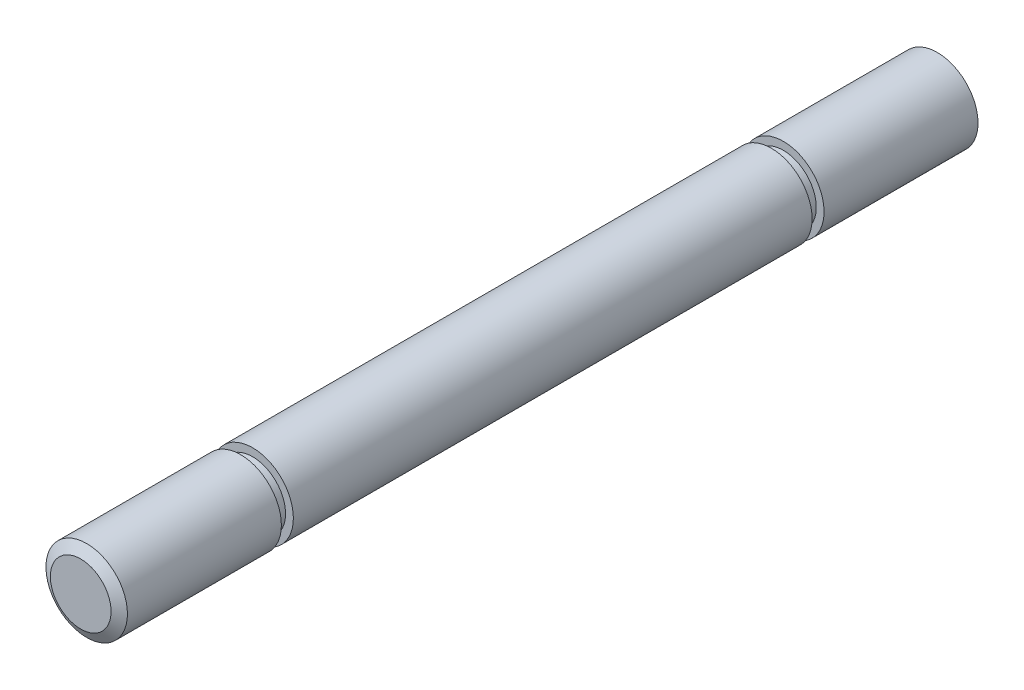
SolidWorks part; units mm, degrees
material "1.2210 (115CrV3)"
ref_plane "Front Plane" through (0, 0, 0) normal (0, 0, 1) x (1, 0, 0)
ref_plane "Top Plane" through (0, 0, 0) normal (0, 1, 0) x (1, 0, 0)
ref_plane "Right Plane" through (0, 0, 0) normal (1, 0, 0) x (0, 0, -1)
sketch "Sketch1" plane through (0, 0, 0) normal (1, 0, 0) x (0, 0, -1)
  line L0 (-36, 0) -> (-36, 3.4)
  line L1 (-36, 3.4) -> (2.4322, 3.4)
  line L5 (2.4322, 3.4) -> (36, 3.4)
  line L6 (36, 3.4) -> (36, 0)
  line L7 (36, 0) -> (-36, 0)
  line L8 (-36, 0) -> (-33.2337, 0) construction
  point P8 (0, 0)
  dimension "D1" = 6.8
  dimension "D2" = 72
revolve "Revolve1" add sketch "Sketch1" angle 360 about L8
chamfer "Chamfer1" distance 0.5 angle 60 2 edges at (0, -3.4, 36) (0, -3.4, -36)
sketch "Sketch2" plane through (0, 0, -36) normal (0, 0, -1) x (-1, 0, 0)
  circle A0 centre (0, 0) radius 2.75
  point P1 (4.7428, 0)
  dimension "D1" = 5.5
extrude "Cut-Extrude1" cut sketch "Sketch2" against normal blind 1 from offset 13.35 flip side to cut offset against normal yes
mirror "Mirror1" about plane through (0, 0, 0) normal (0, 0, 1) of "Cut-Extrude1"
